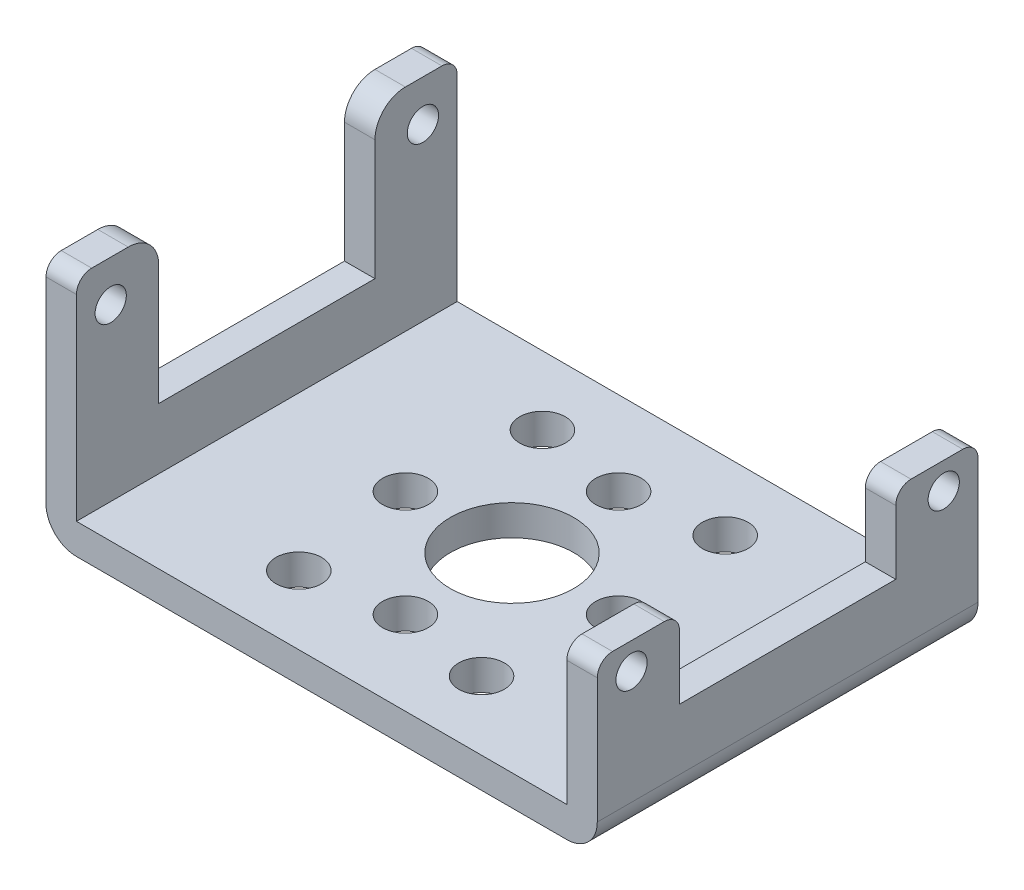
SolidWorks part; units mm, degrees
ref_plane "前视基准面" through (0, 0, 0) normal (0, 0, 1) x (1, 0, 0)
ref_plane "上视基准面" through (0, 0, 0) normal (0, 1, 0) x (1, 0, 0)
ref_plane "右视基准面" through (0, 0, 0) normal (1, 0, 0) x (0, 0, -1)
sketch "草图1" plane through (0, 0, 0) normal (0, 0, 1) x (1, 0, 0)
  line L0 (2, 0) -> (34.2, 0)
  line L1 (18.1, 0) -> (18.1, 2) construction
  line L2 (2, 2) -> (34.2, 2)
  line L3 (34.2, 2) -> (34.2, 11.2)
  line L4 (34.2, 11.2) -> (36.2, 11.2)
  line L5 (36.2, 11.2) -> (36.2, 2)
  line L6 (2, 2) -> (2, 15.9)
  line L7 (2, 15.9) -> (0, 15.9)
  line L8 (0, 15.9) -> (0, 2)
  arc A0 (34.2, 0) -> (36.2, 2) centre (34.2, 2) ccw
  arc A1 (2, 0) -> (0, 2) centre (2, 2) cw
  point P8 (18.1, 2)
  point P14 (36.2, 0)
  point P17 (0, 0)
  dimension "D6" = 2
  dimension "D1" = 36.2
  dimension "D2" = 2
  dimension "D3" = 16.1
  dimension "D4" = 9.2
  dimension "D5" = 13.9
extrude "凸台-拉伸1" add sketch "草图1" along normal blind 25
sketch "草图2" plane through (0, 0, 0) normal (-1, 0, 0) x (0, 0, 1)
  line L1 (25, 15.9) -> (0, 15.9) construction
  line L2 (0, 14.9) -> (0, 15.9)
  line L4 (19.6, 6) -> (19.6, 13.9)
  line L5 (19.6, 6) -> (5.4, 6)
  line L6 (5.4, 6) -> (5.4, 13.9)
  line L7 (0, 15.9) -> (1, 15.9)
  line L8 (3.4, 15.9) -> (21.6, 15.9)
  line L10 (24, 15.9) -> (25, 15.9)
  line L12 (25, 15.9) -> (25, 14.9)
  arc A0 (21.6, 15.9) -> (19.6, 13.9) centre (21.6, 13.9) ccw
  arc A1 (3.4, 15.9) -> (5.4, 13.9) centre (3.4, 13.9) cw
  arc A2 (24, 15.9) -> (25, 14.9) centre (24, 14.9) cw
  arc A3 (1, 15.9) -> (0, 14.9) centre (1, 14.9) ccw
  circle A4 centre (2.25, 13.2) radius 1.025
  circle A5 centre (22.75, 13.2) radius 1.025
  point P5 (12.5, 15.9)
  point P11 (19.6, 15.9)
  point P24 (25, 15.9)
  point P27 (0, 15.9)
  point P31 (12.5, 13.2)
  line M1 (0, 15.9) -> (0, 2)
  line M3 (25, 2) -> (25, 15.9)
  line M4 (25, 15.9) -> (0, 15.9)
  dimension "D1" = 2
  dimension "D2" = 1
  dimension "D4" = 2.05
  dimension "D5" = 2.05
extrude "切除-拉伸1" cut sketch "草图2" against normal blind 50 contours A3 M4 M1 | A4 | A1 L6 L5 L4 A0 M4 | A5 | A2 M4 M3
fillet "圆角1" radius 1 4 edges at (35.2, 11.2, 25) (35.2, 11.2, 19.6) (35.2, 11.2, 0) (35.2, 11.2, 5.4)
sketch "草图3" plane through (36.2, 0, 0) normal (1, 0, 0) x (0, 0, -1)
  line L0 (-12.5, 0) -> (-12.5, 10.736) construction
  line L3 (-25, 0) -> (0, 0) construction
  circle A0 centre (-22.75, 9.45) radius 1.025
  circle A1 centre (-2.25, 9.45) radius 1.025
  dimension "D1" = 2.05
extrude "切除-拉伸2" cut sketch "草图3" against normal blind 6
sketch "草图4" plane through (0, 2, 0) normal (0, 1, 0) x (1, 0, 0)
  line L0 (0, -12.5) -> (36.2, -12.5) construction
  line L1 (0, -19.6) -> (0, -5.4) construction
  line L2 (36.2, -19.6) -> (36.2, -5.4) construction
  circle A0 centre (18.1, -12.5) radius 4.05
  circle A2 centre (18.1, -5.5) radius 1.5
  circle A3 centre (25.1, -12.5) radius 1.5
  circle A4 centre (18.1, -19.5) radius 1.5
  circle A5 centre (11.1, -12.5) radius 1.5
  circle A6 centre (12.1, -4.5) radius 1.5
  circle A7 centre (24.1, -4.5) radius 1.5
  circle A8 centre (24.1, -20.5) radius 1.5
  circle A9 centre (12.1, -20.5) radius 1.5
  dimension "D1" = 8.1
  dimension "D3" = 3
  dimension "D7" = 3
  dimension "D8" = 3
  dimension "D9" = 3
  dimension "D10" = 3
  dimension "D5" = 16
  dimension "D6" = 12
  dimension "D4" = 4
extrude "切除-拉伸3" cut sketch "草图4" against normal blind 10
